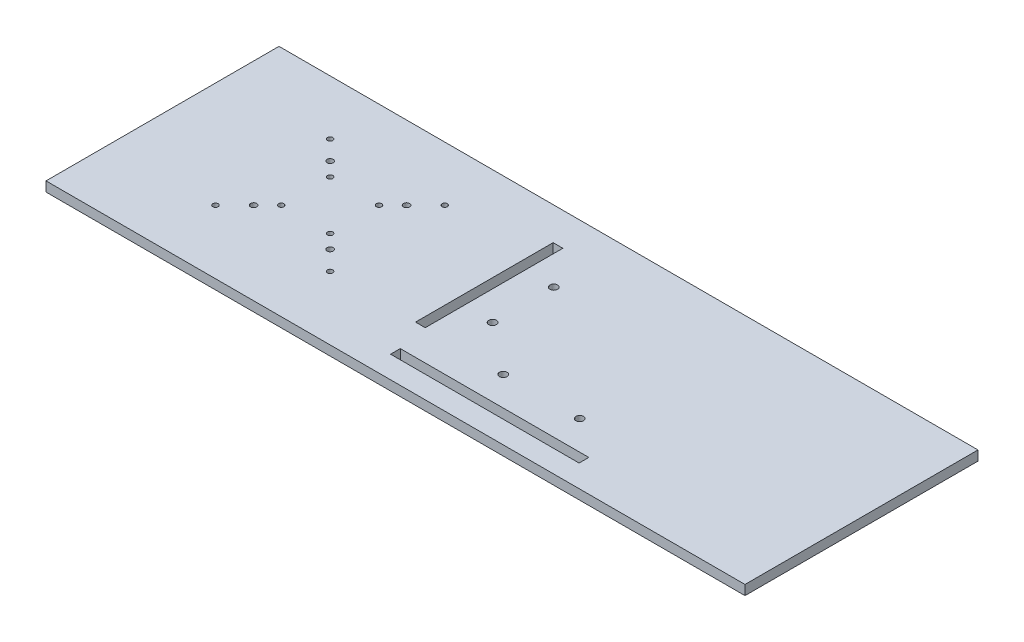
SolidWorks part; units mm, degrees
ref_plane "Front Plane" through (0, 0, 0) normal (0, 0, 1) x (1, 0, 0)
ref_plane "Top Plane" through (0, 0, 0) normal (0, 1, 0) x (1, 0, 0)
ref_plane "Right Plane" through (0, 0, 0) normal (1, 0, 0) x (0, 0, -1)
sketch "Sketch1" plane through (0, 0, 0) normal (0, 1, 0) x (1, 0, 0)
  line L0 (226.25, 105.86) -> (226.25, 65.86) construction
  line L1 (0, 0) -> (457.2, 0)
  line L2 (0, 0) -> (0, 152.4)
  line L3 (0, 152.4) -> (457.2, 152.4)
  line L4 (457.2, 0) -> (457.2, 152.4)
  line L5 (90.7026, 95.13) -> (122.7026, 95.13) construction
  line L6 (90.7026, 95.13) -> (90.7026, 63.13) construction
  line L7 (90.7026, 63.13) -> (122.7026, 63.13) construction
  line L8 (122.7026, 95.13) -> (122.7026, 63.13) construction
  line L9 (144.2026, 116.63) -> (69.2026, 116.63) construction
  line L10 (144.2026, 116.63) -> (144.2026, 41.63) construction
  line L11 (144.2026, 41.63) -> (69.2026, 41.63) construction
  line L12 (69.2026, 116.63) -> (69.2026, 41.63) construction
  line L13 (210.85, 20.86) -> (207.2, 20.86) construction
  line L15 (200.85, 130.86) -> (207.2, 130.86) construction
  line L16 (207.2, 20.86) -> (207.2, 130.86) construction
  line L17 (210.85, 20.86) -> (334.17, 20.86)
  line L18 (210.85, 20.86) -> (210.85, 14.51)
  line L19 (210.85, 14.51) -> (334.17, 14.51)
  line L20 (334.17, 20.86) -> (334.17, 14.51)
  line L21 (207.2, 130.86) -> (200.85, 130.86)
  line L22 (207.2, 130.86) -> (207.2, 40.86)
  line L23 (207.2, 40.86) -> (200.85, 40.86)
  line L24 (200.85, 130.86) -> (200.85, 40.86)
  line L26 (334.17, 52.61) -> (244.17, 52.61) construction
  line L27 (334.17, 52.61) -> (334.17, 20.86) construction
  line L28 (334.17, 20.86) -> (244.17, 20.86) construction
  line L29 (244.17, 52.61) -> (244.17, 20.86) construction
  line L30 (207.2, 115.86) -> (238.95, 115.86) construction
  line L31 (207.2, 115.86) -> (207.2, 55.86) construction
  line L32 (207.2, 55.86) -> (238.95, 55.86) construction
  line L33 (238.95, 115.86) -> (238.95, 55.86) construction
  line L34 (131.7026, 54.13) -> (81.7026, 54.13) construction
  line L35 (131.7026, 54.13) -> (131.7026, 104.13) construction
  line L36 (131.7026, 104.13) -> (81.7026, 104.13) construction
  line L37 (81.7026, 54.13) -> (81.7026, 104.13) construction
  line L38 (131.7026, 54.13) -> (81.7026, 104.13) construction
  line L39 (131.7026, 104.13) -> (81.7026, 54.13) construction
  circle A0 centre (90.7026, 95.13) radius 1.75
  circle A1 centre (122.7026, 95.13) radius 1.75
  circle A2 centre (122.7026, 63.13) radius 1.75
  circle A3 centre (90.7026, 63.13) radius 1.75
  circle A4 centre (69.2026, 116.63) radius 1.75
  circle A5 centre (144.2026, 116.63) radius 1.75
  circle A6 centre (144.2026, 41.63) radius 1.75
  circle A7 centre (69.2026, 41.63) radius 1.75
  circle A8 centre (226.25, 65.86) radius 2.5
  circle A9 centre (226.25, 105.86) radius 2.5
  circle A10 centre (259.17, 39.91) radius 2.5
  circle A11 centre (309.17, 39.91) radius 2.5
  circle A12 centre (81.7026, 104.13) radius 2
  circle A13 centre (131.7026, 104.13) radius 2
  circle A14 centre (131.7026, 54.13) radius 2
  circle A15 centre (81.7026, 54.13) radius 2
  point P14 (122.7026, 79.13)
  point P20 (106.7026, 116.63)
  point P21 (106.7026, 95.13)
  point P23 (144.2026, 79.13)
  point P31 (106.7026, 63.13)
  point P32 (106.7026, 79.13)
  point P35 (0, 0)
  point P42 (226.25, 85.86)
  point P46 (207.2, 85.86)
  point P47 (106.7026, 79.13)
  point P61 (231.6853, 105.86)
  point P62 (0, 0)
  point P63 (102.9248, 76.2)
  point P70 (0, 0)
  point P71 (91.823, 83.379)
  point P72 (106.6953, 78.1422)
  dimension "D3" = 3.5
  dimension "D4" = 3.5
  dimension "D5" = 3.5
  dimension "D6" = 3.5
  dimension "D12" = 3.5
  dimension "D13" = 3.5
  dimension "D14" = 3.5
  dimension "D15" = 3.5
  dimension "D22" = 5
  dimension "D23" = 5
  dimension "D24" = 5
  dimension "D25" = 5
  dimension "D38" = 4
  dimension "D1" = 457.2
  dimension "D2" = 152.4
  dimension "D7" = 32
  dimension "D8" = 32
  dimension "D10" = 75
  dimension "D11" = 75
  dimension "D16" = 6.35
  dimension "D18" = 6.35
  dimension "D19" = 123.32
  dimension "D21" = 90
  dimension "D17" = 20
  dimension "D28" = 19.05
  dimension "D29" = 19.05
  dimension "D30" = 50
  dimension "D31" = 40
  dimension "D26" = 31.75
  dimension "D27" = 90
  dimension "D33" = 25
  dimension "D34" = 31.75
  dimension "D35" = 60
  dimension "D36" = 10
  dimension "D32" = 50
  dimension "D37" = 50
  dimension "D41" = 10
  dimension "D42" = 19.05
  dimension "D43" = 250
  dimension "D39" = 2
  dimension "D40" = 2
extrude "Boss-Extrude1" add sketch "Sketch1" along normal blind 6.35
equation "\"D6@Sketch1\"=\"D3@Sketch1\""
equation "\"D8@Sketch1\"=\"D7@Sketch1\""
equation "\"D12@Sketch1\"=\"D3@Sketch1\""
equation "\"D13@Sketch1\"=\"D12@Sketch1\""
equation "\"D14@Sketch1\"=\"D12@Sketch1\""
equation "\"D15@Sketch1\"=\"D3@Sketch1\""
equation "\"D23@Sketch1\"=\"D22@Sketch1\""
equation "\"D24@Sketch1\"=\"D23@Sketch1\""
equation "\"D25@Sketch1\"=\"D22@Sketch1\""
equation "\"D28@Sketch1\"=.75in"
equation "\"D29@Sketch1\"=.75in"
